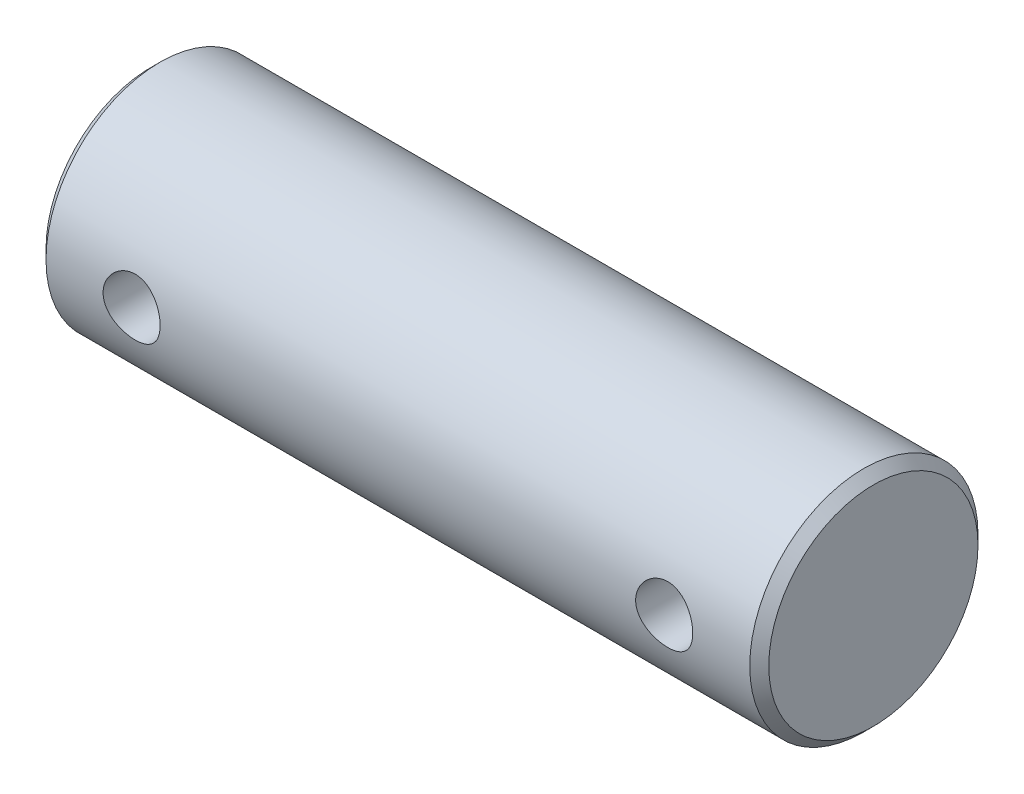
SolidWorks part; units mm, degrees
ref_plane "Front Plane" through (0, 0, 0) normal (0, 0, 1) x (1, 0, 0)
ref_plane "Top Plane" through (0, 0, 0) normal (0, 1, 0) x (1, 0, 0)
ref_plane "Right Plane" through (0, 0, 0) normal (1, 0, 0) x (0, 0, -1)
sketch "Sketch1" plane through (0, 0, 0) normal (1, 0, 0) x (0, 0, -1)
  circle A0 centre (0, 0) radius 6
  dimension "D1" = 12
extrude "Boss-Extrude1" add sketch "Sketch1" along normal blind 38
chamfer "Chamfer1" distance 0.5 angle 45 2 edges at (0, 0, -6) (38, 0, -6)
sketch "Sketch2" plane through (0, 0, 0) normal (0, 0, 1) x (1, 0, 0)
  line L0 (0, 5.5) -> (0, -5.5) construction
  line L1 (38, -5.5) -> (38, 5.5) construction
  circle A0 centre (5, 0) radius 1.5
  circle A1 centre (33, 0) radius 1.5
  dimension "D1" = 3
  dimension "D2" = 5
  dimension "D3" = 5
extrude "Cut-Extrude1" cut sketch "Sketch2" against normal through all both and the other way through all
